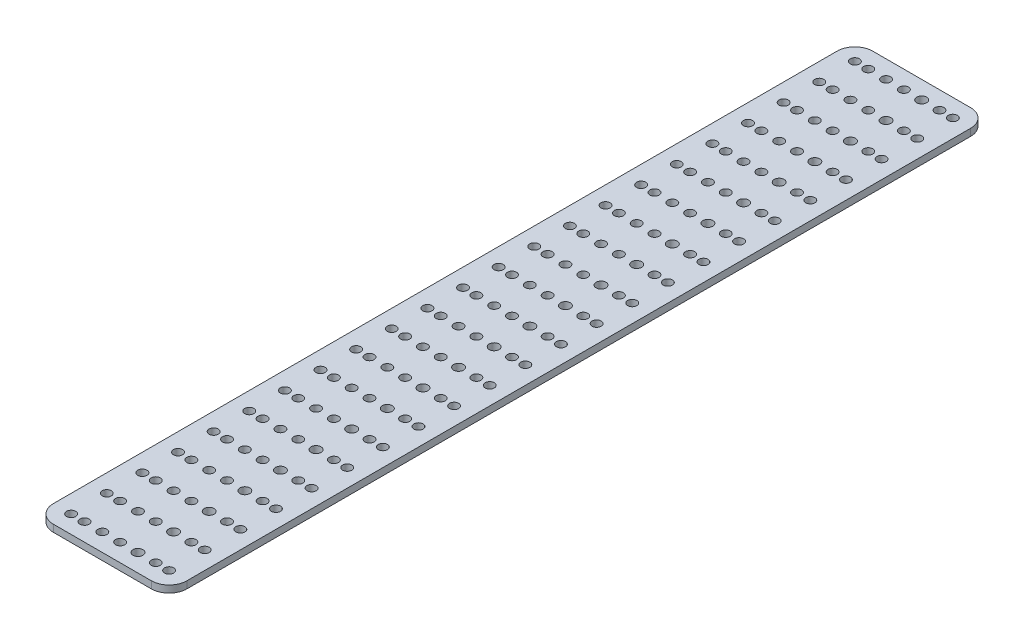
SolidWorks part; units mm, degrees
ref_plane "Front Plane" through (0, 0, 0) normal (0, 0, 1) x (1, 0, 0)
ref_plane "Top Plane" through (0, 0, 0) normal (0, 1, 0) x (1, 0, 0)
ref_plane "Right Plane" through (0, 0, 0) normal (1, 0, 0) x (0, 0, -1)
sketch "Sketch2" plane through (0, 0, 0) normal (0, 1, 0) x (1, 0, 0)
  line L0 (0, 184) -> (0, -49816) construction
  line L1 (-30, 184) -> (30, 184)
  line L2 (-30, 184) -> (-30, -184)
  line L3 (-30, -184) -> (30, -184)
  line L4 (30, 184) -> (30, -184)
  line L5 (-30, 184) -> (30, -184) construction
  line L6 (-30, -184) -> (30, 184) construction
  line L7 (-30, 184) -> (-22, 184) construction
  line L8 (-30, 184) -> (-30, 176) construction
  line L9 (-30, 176) -> (-22, 176) construction
  line L10 (-22, 184) -> (-22, 176) construction
  line L11 (0, 0) -> (50000, 0) construction
  line L12 (-16, 183.7742) -> (-16, -49816.2258) construction
  line L13 (16, 183.7742) -> (16, -49816.2258) construction
  line L14 (-22, 176) -> (49978, 176) construction
  circle A0 centre (-22, 176) radius 2.05
  circle A1 centre (-16, 176) radius 2.05
  circle A2 centre (0, 176) radius 2.05
  circle A3 centre (16, 176) radius 2.05
  circle A4 centre (22, 176) radius 2.05
  circle A5 centre (-8, 176) radius 2.05
  circle A6 centre (8, 176) radius 2.2188
  circle A7 centre (22, 160) radius 2.05
  circle A8 centre (16, 160) radius 2.05
  circle A9 centre (8, 160) radius 2.2188
  circle A10 centre (0, 160) radius 2.05
  circle A11 centre (-8, 160) radius 2.05
  circle A12 centre (-16, 160) radius 2.05
  circle A13 centre (-22, 160) radius 2.05
  circle A14 centre (22, 144) radius 2.05
  circle A15 centre (16, 144) radius 2.05
  circle A16 centre (8, 144) radius 2.2188
  circle A17 centre (0, 144) radius 2.05
  circle A18 centre (-8, 144) radius 2.05
  circle A19 centre (-16, 144) radius 2.05
  circle A20 centre (-22, 144) radius 2.05
  circle A21 centre (22, 128) radius 2.05
  circle A22 centre (16, 128) radius 2.05
  circle A23 centre (8, 128) radius 2.2188
  circle A24 centre (0, 128) radius 2.05
  circle A25 centre (-8, 128) radius 2.05
  circle A26 centre (-16, 128) radius 2.05
  circle A27 centre (-22, 128) radius 2.05
  circle A28 centre (22, 112) radius 2.05
  circle A29 centre (16, 112) radius 2.05
  circle A30 centre (8, 112) radius 2.2188
  circle A31 centre (0, 112) radius 2.05
  circle A32 centre (-8, 112) radius 2.05
  circle A33 centre (-16, 112) radius 2.05
  circle A34 centre (-22, 112) radius 2.05
  circle A35 centre (22, 96) radius 2.05
  circle A36 centre (16, 96) radius 2.05
  circle A37 centre (8, 96) radius 2.2188
  circle A38 centre (0, 96) radius 2.05
  circle A39 centre (-8, 96) radius 2.05
  circle A40 centre (-16, 96) radius 2.05
  circle A41 centre (-22, 96) radius 2.05
  circle A42 centre (22, 80) radius 2.05
  circle A43 centre (16, 80) radius 2.05
  circle A44 centre (8, 80) radius 2.2188
  circle A45 centre (0, 80) radius 2.05
  circle A46 centre (-8, 80) radius 2.05
  circle A47 centre (-16, 80) radius 2.05
  circle A48 centre (-22, 80) radius 2.05
  circle A49 centre (22, 64) radius 2.05
  circle A50 centre (16, 64) radius 2.05
  circle A51 centre (8, 64) radius 2.2188
  circle A52 centre (0, 64) radius 2.05
  circle A53 centre (-8, 64) radius 2.05
  circle A54 centre (-16, 64) radius 2.05
  circle A55 centre (-22, 64) radius 2.05
  circle A56 centre (22, 48) radius 2.05
  circle A57 centre (16, 48) radius 2.05
  circle A58 centre (8, 48) radius 2.2188
  circle A59 centre (0, 48) radius 2.05
  circle A60 centre (-8, 48) radius 2.05
  circle A61 centre (-16, 48) radius 2.05
  circle A62 centre (-22, 48) radius 2.05
  circle A63 centre (22, 32) radius 2.05
  circle A64 centre (16, 32) radius 2.05
  circle A65 centre (8, 32) radius 2.2188
  circle A66 centre (0, 32) radius 2.05
  circle A67 centre (-8, 32) radius 2.05
  circle A68 centre (-16, 32) radius 2.05
  circle A69 centre (-22, 32) radius 2.05
  circle A70 centre (22, 16) radius 2.05
  circle A71 centre (16, 16) radius 2.05
  circle A72 centre (8, 16) radius 2.2188
  circle A73 centre (0, 16) radius 2.05
  circle A74 centre (-8, 16) radius 2.05
  circle A75 centre (-16, 16) radius 2.05
  circle A76 centre (-22, 16) radius 2.05
  circle A77 centre (22, 0) radius 2.05
  circle A78 centre (16, 0) radius 2.05
  circle A79 centre (8, 0) radius 2.2188
  circle A80 centre (0, 0) radius 2.05
  circle A81 centre (-8, 0) radius 2.05
  circle A82 centre (-16, 0) radius 2.05
  circle A83 centre (-22, 0) radius 2.05
  circle A84 centre (22, -16) radius 2.05
  circle A85 centre (16, -16) radius 2.05
  circle A86 centre (8, -16) radius 2.2188
  circle A87 centre (0, -16) radius 2.05
  circle A88 centre (-8, -16) radius 2.05
  circle A89 centre (-16, -16) radius 2.05
  circle A90 centre (-22, -16) radius 2.05
  circle A91 centre (22, -32) radius 2.05
  circle A92 centre (16, -32) radius 2.05
  circle A93 centre (8, -32) radius 2.2188
  circle A94 centre (0, -32) radius 2.05
  circle A95 centre (-8, -32) radius 2.05
  circle A96 centre (-16, -32) radius 2.05
  circle A97 centre (-22, -32) radius 2.05
  circle A98 centre (22, -48) radius 2.05
  circle A99 centre (16, -48) radius 2.05
  circle A100 centre (8, -48) radius 2.2188
  circle A101 centre (0, -48) radius 2.05
  circle A102 centre (-8, -48) radius 2.05
  circle A103 centre (-16, -48) radius 2.05
  circle A104 centre (-22, -48) radius 2.05
  circle A105 centre (22, -64) radius 2.05
  circle A106 centre (16, -64) radius 2.05
  circle A107 centre (8, -64) radius 2.2188
  circle A108 centre (0, -64) radius 2.05
  circle A109 centre (-8, -64) radius 2.05
  circle A110 centre (-16, -64) radius 2.05
  circle A111 centre (-22, -64) radius 2.05
  circle A112 centre (22, -80) radius 2.05
  circle A113 centre (16, -80) radius 2.05
  circle A114 centre (8, -80) radius 2.2188
  circle A115 centre (0, -80) radius 2.05
  circle A116 centre (-8, -80) radius 2.05
  circle A117 centre (-16, -80) radius 2.05
  circle A118 centre (-22, -80) radius 2.05
  circle A119 centre (22, -96) radius 2.05
  circle A120 centre (16, -96) radius 2.05
  circle A121 centre (8, -96) radius 2.2188
  circle A122 centre (0, -96) radius 2.05
  circle A123 centre (-8, -96) radius 2.05
  circle A124 centre (-16, -96) radius 2.05
  circle A125 centre (-22, -96) radius 2.05
  circle A126 centre (22, -112) radius 2.05
  circle A127 centre (16, -112) radius 2.05
  circle A128 centre (8, -112) radius 2.2188
  circle A129 centre (0, -112) radius 2.05
  circle A130 centre (-8, -112) radius 2.05
  circle A131 centre (-16, -112) radius 2.05
  circle A132 centre (-22, -112) radius 2.05
  circle A133 centre (22, -128) radius 2.05
  circle A134 centre (16, -128) radius 2.05
  circle A135 centre (8, -128) radius 2.2188
  circle A136 centre (0, -128) radius 2.05
  circle A137 centre (-8, -128) radius 2.05
  circle A138 centre (-16, -128) radius 2.05
  circle A139 centre (-22, -128) radius 2.05
  circle A140 centre (22, -144) radius 2.05
  circle A141 centre (16, -144) radius 2.05
  circle A142 centre (8, -144) radius 2.2188
  circle A143 centre (0, -144) radius 2.05
  circle A144 centre (-8, -144) radius 2.05
  circle A145 centre (-16, -144) radius 2.05
  circle A146 centre (-22, -144) radius 2.05
  circle A147 centre (22, -160) radius 2.05
  circle A148 centre (16, -160) radius 2.05
  circle A149 centre (8, -160) radius 2.2188
  circle A150 centre (0, -160) radius 2.05
  circle A151 centre (-8, -160) radius 2.05
  circle A152 centre (-16, -160) radius 2.05
  circle A153 centre (-22, -160) radius 2.05
  circle A154 centre (22, -176) radius 2.05
  circle A155 centre (16, -176) radius 2.05
  circle A156 centre (8, -176) radius 2.2188
  circle A157 centre (0, -176) radius 2.05
  circle A158 centre (-8, -176) radius 2.05
  circle A159 centre (-16, -176) radius 2.05
  circle A160 centre (-22, -176) radius 2.05
  point P0 (0, 0)
  point P11 (0, 184)
  dimension "D5" = 4.1
  dimension "D1" = 368
  dimension "D2" = 60
  dimension "D3" = 8
  dimension "D4" = 8
  dimension "D6" = 16
  dimension "D7" = 8
  dimension "D8" = 8
  dimension "D9" = 23
extrude "Boss-Extrude2" add sketch "Sketch2" along normal blind 3.175
fillet "Fillet1" radius 8 4 edges at (30, 1.5875, -184) (-30, 1.5875, -184) (-30, 1.5875, 184) (30, 1.5875, 184)
equation "\"w\" = 60mm"
equation "\"h\"= 368mm"
equation "\"sh\"= 4.1mm"
equation "\"thick\"= 3.175mm"
equation "\"D1@Sketch2\"=\"h\""
equation "\"D2@Sketch2\"=\"w\""
equation "\"D5@Sketch2\"=\"sh\""
equation "\"D1@Boss-Extrude2\"=\"thick\""
